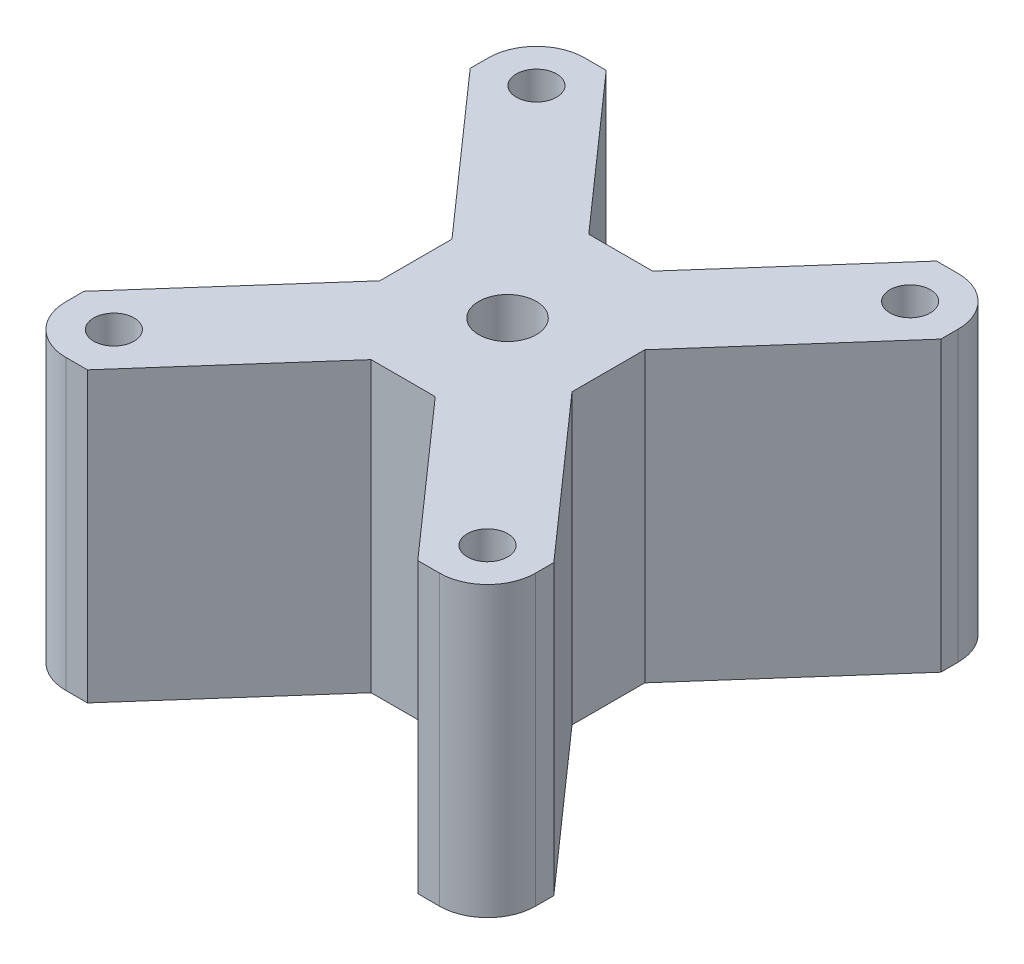
SolidWorks part; units mm, degrees
ref_plane "前视基准面" through (0, 0, 0) normal (0, 0, 1) x (1, 0, 0)
ref_plane "上视基准面" through (0, 0, 0) normal (0, 1, 0) x (1, 0, 0)
ref_plane "右视基准面" through (0, 0, 0) normal (1, 0, 0) x (0, 0, -1)
sketch "草图1" plane through (0, 0, 0) normal (0, 1, 0) x (1, 0, 0)
  line L0 (-11.5869, 9.563) -> (7.8411, -12.409) construction
  line L1 (-9.714, 13.719) -> (9.714, 13.719) construction
  line L2 (-12.214, 11.219) -> (-12.214, -10.753) construction
  line L3 (-9.714, -13.253) -> (9.714, -13.253) construction
  line L4 (12.214, 11.219) -> (12.214, -10.753) construction
  line L9 (-11.5869, -9.097) -> (7.8411, 12.875) construction
  line L10 (-7.8411, 12.875) -> (11.5869, -9.097) construction
  line L11 (11.3154, 9.2992) -> (-7.8395, -12.4072) construction
  line L12 (-9.714, 11.219) -> (9.714, -10.753) construction
  line L13 (-9.714, -10.753) -> (9.714, 11.219) construction
  line L14 (-4.9975, 2.1108) -> (-12.214, 10.2722)
  line L15 (-4.9975, 5.8849) -> (4.9975, 5.8849) construction
  line L16 (-4.9975, 5.8849) -> (-4.9975, -5.4189) construction
  line L17 (-4.9975, -5.4189) -> (4.9975, -5.4189) construction
  line L18 (4.9975, 5.8849) -> (4.9975, -5.4189) construction
  line L19 (-4.9975, 5.8849) -> (4.9975, -5.4189) construction
  line L20 (-4.9975, -5.4189) -> (4.9975, 5.8849) construction
  line L21 (-4.9975, 2.1108) -> (-4.9975, -1.6448)
  line L22 (-4.9975, -1.6448) -> (-12.214, -9.8062)
  line L23 (4.9975, 2.1398) -> (4.9975, -1.6448)
  line L24 (4.9975, -1.6448) -> (12.214, -9.8062)
  line L25 (4.9975, 2.1398) -> (12.214, 10.3175)
  line L26 (-8.5874, 13.719) -> (-1.6604, 5.8849)
  line L27 (-1.6604, 5.8849) -> (1.6604, 5.8849)
  line L28 (1.6604, 5.8849) -> (8.5874, 13.719)
  line L29 (-8.5859, -13.253) -> (-1.6727, -5.4189)
  line L30 (-1.6727, -5.4189) -> (1.6604, -5.4189)
  line L31 (1.6604, -5.4189) -> (8.5874, -13.253)
  line L32 (-9.714, 13.719) -> (-8.5874, 13.719)
  line L33 (-12.214, 10.2722) -> (-12.214, 11.219)
  line L34 (8.5874, 13.719) -> (9.714, 13.719)
  line L35 (12.214, 10.3175) -> (12.214, 11.219)
  line L36 (12.214, -10.753) -> (12.214, -9.8062)
  line L37 (8.5874, -13.253) -> (9.714, -13.253)
  line L38 (-9.714, -13.253) -> (-8.5859, -13.253)
  line L39 (-12.214, -10.753) -> (-12.214, -9.8062)
  arc A1 (-12.214, 11.219) -> (-9.714, 13.719) centre (-9.714, 11.219) cw
  arc A2 (12.214, 11.219) -> (9.714, 13.719) centre (9.714, 11.219) ccw
  arc A3 (-9.714, -13.253) -> (-12.214, -10.753) centre (-9.714, -10.753) cw
  arc A4 (9.714, -13.253) -> (12.214, -10.753) centre (9.714, -10.753) ccw
  circle A5 centre (-9.714, 11.219) radius 1.05
  circle A6 centre (9.714, 11.219) radius 1.05
  circle A7 centre (-9.714, -10.753) radius 1.05
  circle A8 centre (9.714, -10.753) radius 1.05
  circle A9 centre (0, 0) radius 1.5
  circle A10 centre (-9.714, 11.219) radius 2.5 construction
  circle A11 centre (9.714, 11.219) radius 2.5 construction
  circle A12 centre (9.714, -10.753) radius 2.5 construction
  circle A13 centre (-9.714, -10.753) radius 2.5 construction
  point P30 (0, 0.233)
  dimension "D1" = 2.5
  dimension "D2" = 2.5
  dimension "D3" = 2.5
  dimension "D4" = 2.5
extrude "凸台-拉伸3" add sketch "草图1" along normal blind 15 contours A6 | A8 | A7 | A5 | A2 L34 L28 L27 L26 L32 A1 L33 L14 L21 L22 L39 A3 L38 L29 L30 L31 L37 A4 L36 L24 L23 L25 L35 | A9
